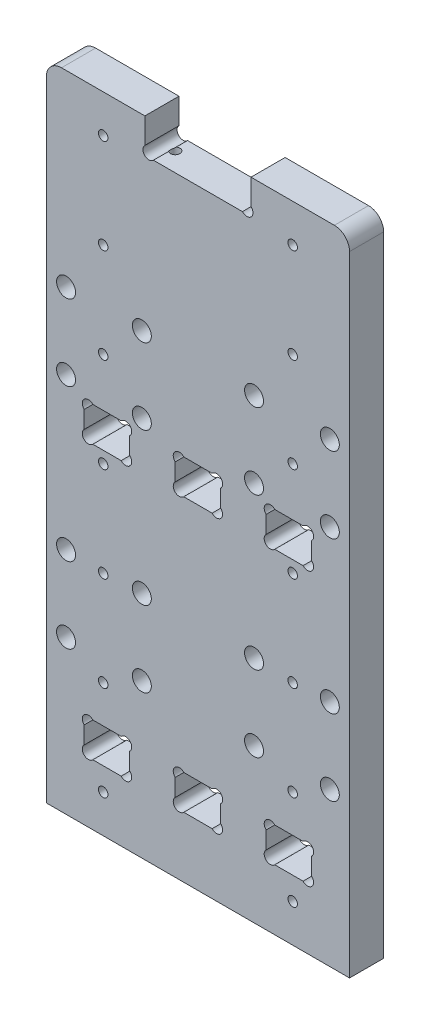
SolidWorks part; units mm, degrees
ref_plane "Front" through (0, 0, 0) normal (0, 0, 1) x (1, 0, 0)
ref_plane "Top" through (0, 0, 0) normal (0, 1, 0) x (1, 0, 0)
ref_plane "Right" through (0, 0, 0) normal (1, 0, 0) x (0, 0, -1)
sketch "Esquisse1" plane through (0, 0, 0) normal (0, 0, 1) x (1, 0, 0)
  line L1 (0, 0) -> (80, 0)
  line L2 (0, 0) -> (0, 170)
  line L3 (0, 170) -> (80, 170)
  line L4 (80, 0) -> (80, 170)
  dimension "D1" = 80
  dimension "D2" = 170
extrude "Boss.-Extru.1" add sketch "Esquisse1" along normal blind 9
sketch "Esquisse2" plane through (0, 0, 9) normal (0, 0, 1) x (1, 0, 0)
  line L0 (40, 0) -> (40, 170) construction
  line L1 (0, 0) -> (80, 0) construction
  line L2 (80, 170) -> (0, 170) construction
  line L3 (15, 10) -> (15, 35) construction
  circle A0 centre (15, 10) radius 1.25
  circle A1 centre (65, 10) radius 1.25
  circle A2 centre (15, 35) radius 1.25
  circle A3 centre (65, 35) radius 1.25
  circle A4 centre (15, 60) radius 1.25
  circle A5 centre (65, 60) radius 1.25
  circle A6 centre (15, 85) radius 1.25
  circle A7 centre (65, 85) radius 1.25
  circle A8 centre (15, 110) radius 1.25
  circle A9 centre (65, 110) radius 1.25
  circle A10 centre (15, 135) radius 1.25
  circle A11 centre (65, 135) radius 1.25
  circle A12 centre (15, 160) radius 1.25
  circle A13 centre (65, 160) radius 1.25
  circle A14 centre (15, 185) radius 1.25
  circle A15 centre (65, 185) radius 1.25
  dimension "D2" = 2.5
  dimension "D1" = 50
  dimension "D3" = 10
  dimension "D5" = 25
  dimension "D4" = 8
extrude "Enlèv. mat.-Extru.1" cut sketch "Esquisse2" against normal through all
sketch "Esquisse4" plane through (0, 0, 9) normal (0, 0, 1) x (1, 0, 0)
  line L0 (40, 170) -> (40, 161) construction
  line L1 (80, 170) -> (0, 170) construction
  line L2 (54, 161) -> (26, 161)
  line L3 (26, 161) -> (26, 170)
  line L4 (26, 170) -> (54, 170)
  line L5 (54, 161) -> (54, 170)
  dimension "D1" = 28
  dimension "D2" = 9
extrude "Enlèv. mat.-Extru.3" cut sketch "Esquisse4" against normal through all
sketch "Esquisse5" plane through (0, 161, 0) normal (0, 1, 0) x (1, 0, 0)
  line L0 (29, 0) -> (29, -4) construction
  line L1 (26, 0) -> (54, 0) construction
  line L2 (40, 0) -> (40, -4.3659) construction
  circle A0 centre (29, -4) radius 1.25
  circle A1 centre (51, -4) radius 1.25
  dimension "D1" = 2.5
  dimension "D2" = 4
  dimension "D3" = 22
extrude "Enlèv. mat.-Extru.4" cut sketch "Esquisse5" against normal blind 10
sketch "Esquisse6" plane through (0, 0, 9) normal (0, 0, 1) x (1, 0, 0)
  line L0 (74.8, 120.5) -> (74.8, 80.5) construction
  line L1 (40, 161) -> (40, 0) construction
  line L2 (26, 161) -> (54, 161) construction
  line L3 (0, 0) -> (80, 0) construction
  line L5 (74.8, 80.5) -> (40, 80.5) construction
  line L6 (5.2, 120.5) -> (5.2, 80.5) construction
  line L7 (74.8, 120.5) -> (64.8, 120.5) construction
  line L8 (64.8, 120.5) -> (64.8, 124.5729) construction
  circle A0 centre (74.8, 120.5) radius 2.5
  circle A1 centre (74.8, 60.5) radius 2.5
  circle A2 centre (74.8, 100.5) radius 2.5
  circle A3 centre (74.8, 40.5) radius 2.5
  circle A4 centre (5.2, 40.5) radius 2.5
  circle A5 centre (5.2, 100.5) radius 2.5
  circle A6 centre (5.2, 60.5) radius 2.5
  circle A7 centre (5.2, 120.5) radius 2.5
  circle A8 centre (54.8, 100.5) radius 2.5
  circle A9 centre (54.8, 120.5) radius 2.5
  circle A10 centre (54.8, 40.5) radius 2.5
  circle A11 centre (54.8, 60.5) radius 2.5
  circle A12 centre (25.2, 60.5) radius 2.5
  circle A13 centre (25.2, 40.5) radius 2.5
  circle A14 centre (25.2, 120.5) radius 2.5
  circle A15 centre (25.2, 100.5) radius 2.5
  dimension "D3" = 5
  dimension "D5" = 20
  dimension "D1" = 34.8
  dimension "D2" = 20
  dimension "D4" = 20
extrude "Enlèv. mat.-Extru.5" cut sketch "Esquisse6" against normal through all
fillet "Congé1" radius 4 2 edges at (80, 170, 4.5) (0, 170, 4.5)
sketch "Esquisse7" plane through (0, 0, 9) normal (0, 0, 1) x (1, 0, 0)
  line L0 (40, 0) -> (40, 161) construction
  line L1 (10, 25.1) -> (22, 25.1)
  line L2 (10, 25.1) -> (10, 16)
  line L3 (10, 16) -> (22, 16)
  line L4 (22, 25.1) -> (22, 16)
  line L5 (0, 0) -> (80, 0) construction
  line L6 (26, 161) -> (54, 161) construction
  line L7 (46, 25.1) -> (34, 25.1)
  line L8 (34, 25.1) -> (34, 16)
  line L9 (34, 16) -> (46, 16)
  line L10 (46, 25.1) -> (46, 16)
  line L11 (58, 25.1) -> (58, 16)
  line L12 (70, 16) -> (58, 16)
  line L13 (70, 25.1) -> (70, 16)
  line L14 (70, 25.1) -> (58, 25.1)
  line L15 (16, 25.1) -> (16, 88.1) construction
  line L16 (16, 56.6) -> (27.6071, 56.6) construction
  line L17 (70, 88.1) -> (58, 88.1)
  line L18 (70, 88.1) -> (70, 97.2)
  line L19 (70, 97.2) -> (58, 97.2)
  line L20 (58, 88.1) -> (58, 97.2)
  line L21 (46, 88.1) -> (46, 97.2)
  line L22 (34, 97.2) -> (46, 97.2)
  line L23 (34, 88.1) -> (34, 97.2)
  line L24 (46, 88.1) -> (34, 88.1)
  line L25 (22, 88.1) -> (22, 97.2)
  line L26 (10, 97.2) -> (22, 97.2)
  line L27 (10, 88.1) -> (10, 97.2)
  line L28 (10, 88.1) -> (22, 88.1)
  point P14 (34, 20.55)
  point P16 (40, 16)
  point P17 (40, 25.1)
  point P37 (40, 88.1)
  point P38 (40, 97.2)
  dimension "D1" = 12
  dimension "D2" = 12
  dimension "D3" = 12
  dimension "D4" = 16
  dimension "D5" = 9.1
  dimension "D6" = 63
extrude "Enlèv. mat.-Extru.6" cut sketch "Esquisse7" against normal through all
sketch "Esquisse8" plane through (0, 0, 9) normal (0, 0, 1) x (1, 0, 0)
  line L0 (10, 16) -> (10, 15.9) construction
  line L1 (10, 16) -> (9.9, 16) construction
  line L2 (10, 16) -> (11.0803, 17.0803) construction
  line L3 (10, 16) -> (22, 16) construction
  line L4 (16, 16) -> (16, 25.1) construction
  line L5 (22, 25.1) -> (10, 25.1) construction
  line L6 (16, 20.55) -> (10, 20.55) construction
  line L7 (10, 25.1) -> (10, 16) construction
  line L8 (10, 25.1) -> (11.0803, 24.0197) construction
  line L9 (10, 25.1) -> (9.9, 25.1) construction
  line L10 (10, 25.1) -> (10, 25.2) construction
  line L11 (22, 25.1) -> (22, 25.2) construction
  line L12 (22, 25.1) -> (22.1, 25.1) construction
  line L13 (22, 25.1) -> (20.9197, 24.0197) construction
  line L14 (22, 16) -> (20.9197, 17.0803) construction
  line L15 (22, 16) -> (22.1, 16) construction
  line L16 (22, 16) -> (22, 15.9) construction
  line L17 (22, 20.55) -> (34, 20.55) construction
  line L18 (22, 16) -> (22, 25.1) construction
  line L19 (34, 25.1) -> (34, 16) construction
  line L20 (40, 16) -> (40, 25.1) construction
  line L21 (34, 16) -> (46, 16) construction
  line L22 (46, 25.1) -> (34, 25.1) construction
  line L23 (28, 20.55) -> (28, 29.7274) construction
  line L24 (34, 16) -> (34, 15.9) construction
  line L25 (34, 16) -> (33.9, 16) construction
  line L26 (34, 16) -> (35.0803, 17.0803) construction
  line L27 (34, 25.1) -> (35.0803, 24.0197) construction
  line L28 (34, 25.1) -> (33.9, 25.1) construction
  line L29 (34, 25.1) -> (34, 25.2) construction
  line L30 (46, 25.1) -> (46, 25.2) construction
  line L31 (46, 25.1) -> (46.1, 25.1) construction
  line L32 (46, 25.1) -> (44.9197, 24.0197) construction
  line L33 (46, 16) -> (44.9197, 17.0803) construction
  line L34 (46, 16) -> (46.1, 16) construction
  line L35 (46, 16) -> (46, 15.9) construction
  line L36 (58, 20.55) -> (46, 20.55) construction
  line L37 (58, 16) -> (58, 15.9) construction
  line L38 (58, 16) -> (57.9, 16) construction
  line L39 (58, 16) -> (59.0803, 17.0803) construction
  line L40 (58, 25.1) -> (59.0803, 24.0197) construction
  line L41 (58, 25.1) -> (57.9, 25.1) construction
  line L42 (58, 25.1) -> (58, 25.2) construction
  line L43 (70, 25.1) -> (70, 25.2) construction
  line L44 (70, 25.1) -> (70.1, 25.1) construction
  line L45 (70, 25.1) -> (68.9197, 24.0197) construction
  line L46 (64, 20.55) -> (70, 20.55) construction
  line L47 (64, 16) -> (64, 25.1) construction
  line L48 (70, 16) -> (68.9197, 17.0803) construction
  line L49 (70, 16) -> (70.1, 16) construction
  line L50 (70, 16) -> (70, 15.9) construction
  line L51 (16, 25.1) -> (16, 88.1) construction
  line L52 (10, 88.1) -> (22, 88.1) construction
  line L53 (16, 56.6) -> (40, 56.6) construction
  line L54 (70, 97.2) -> (70, 97.3) construction
  line L55 (70, 97.2) -> (70.1, 97.2) construction
  line L56 (70, 97.2) -> (68.9197, 96.1197) construction
  line L57 (64, 97.2) -> (64, 88.1) construction
  line L58 (64, 92.65) -> (70, 92.65) construction
  line L59 (70, 88.1) -> (68.9197, 89.1803) construction
  line L60 (70, 88.1) -> (70.1, 88.1) construction
  line L61 (70, 88.1) -> (70, 88) construction
  line L62 (58, 88.1) -> (58, 88) construction
  line L63 (58, 88.1) -> (57.9, 88.1) construction
  line L64 (58, 88.1) -> (59.0803, 89.1803) construction
  line L65 (58, 97.2) -> (59.0803, 96.1197) construction
  line L66 (58, 97.2) -> (57.9, 97.2) construction
  line L67 (58, 97.2) -> (58, 97.3) construction
  line L68 (58, 92.65) -> (46, 92.65) construction
  line L69 (46, 97.2) -> (46, 97.3) construction
  line L70 (46, 97.2) -> (46.1, 97.2) construction
  line L71 (46, 97.2) -> (44.9197, 96.1197) construction
  line L72 (46, 88.1) -> (44.9197, 89.1803) construction
  line L73 (46, 88.1) -> (46.1, 88.1) construction
  line L74 (46, 88.1) -> (46, 88) construction
  line L75 (34, 88.1) -> (34, 88) construction
  line L76 (34, 88.1) -> (33.9, 88.1) construction
  line L77 (34, 88.1) -> (35.0803, 89.1803) construction
  line L78 (34, 97.2) -> (35.0803, 96.1197) construction
  line L79 (34, 97.2) -> (33.9, 97.2) construction
  line L80 (34, 97.2) -> (34, 97.3) construction
  line L81 (40, 97.2) -> (40, 88.1) construction
  line L82 (22, 92.65) -> (34, 92.65) construction
  line L83 (22, 97.2) -> (22, 97.3) construction
  line L84 (22, 97.2) -> (22.1, 97.2) construction
  line L86 (22, 88.1) -> (20.9197, 89.1803) construction
  line L87 (22, 88.1) -> (22.1, 88.1) construction
  line L88 (22, 88.1) -> (22, 88) construction
  line L89 (10, 88.1) -> (10, 88) construction
  line L90 (10, 88.1) -> (9.9, 88.1) construction
  line L91 (10, 88.1) -> (11.0803, 89.1803) construction
  line L92 (16, 92.65) -> (10, 92.65) construction
  line L93 (16, 97.2) -> (16, 88.1) construction
  line L94 (10, 97.2) -> (11.0803, 96.1197) construction
  line L95 (10, 97.2) -> (9.9, 97.2) construction
  line L96 (10, 97.2) -> (10, 97.3) construction
  line L97 (26, 161) -> (26, 160.9) construction
  line L98 (26, 161) -> (25.9, 161) construction
  line L99 (40, 161) -> (40, 171.5112) construction
  line L100 (26, 161) -> (54, 161) construction
  line L101 (54, 161) -> (54.1, 161) construction
  line L102 (54, 161) -> (54, 160.9) construction
  circle A0 centre (11.0803, 17.0803) radius 1.6
  circle A1 centre (11.0803, 24.0197) radius 1.6
  circle A2 centre (20.9197, 24.0197) radius 1.6
  circle A3 centre (20.9197, 17.0803) radius 1.6
  circle A4 centre (35.0803, 17.0803) radius 1.6
  circle A5 centre (35.0803, 24.0197) radius 1.6
  circle A6 centre (44.9197, 24.0197) radius 1.6
  circle A7 centre (44.9197, 17.0803) radius 1.6
  circle A8 centre (59.0803, 17.0803) radius 1.6
  circle A9 centre (59.0803, 24.0197) radius 1.6
  circle A10 centre (68.9197, 24.0197) radius 1.6
  circle A11 centre (68.9197, 17.0803) radius 1.6
  circle A12 centre (68.9197, 96.1197) radius 1.6
  circle A13 centre (68.9197, 89.1803) radius 1.6
  circle A14 centre (59.0803, 89.1803) radius 1.6
  circle A15 centre (59.0803, 96.1197) radius 1.6
  circle A16 centre (44.9197, 96.1197) radius 1.6
  circle A17 centre (44.9197, 89.1803) radius 1.6
  circle A18 centre (35.0803, 89.1803) radius 1.6
  circle A19 centre (35.0803, 96.1197) radius 1.6
  circle A20 centre (20.9197, 96.1197) radius 1.6
  circle A21 centre (20.9197, 89.1803) radius 1.6
  circle A22 centre (11.0803, 89.1803) radius 1.6
  circle A23 centre (11.0803, 96.1197) radius 1.6
  circle A24 centre (27.0803, 162.0803) radius 1.6
  circle A25 centre (52.9197, 162.0803) radius 1.6
  point P184 (22, 97.2)
  point P186 (10, 97.2)
  point P188 (10, 88.1)
  point P190 (34, 97.2)
  point P192 (58, 97.2)
  point P194 (70, 97.2)
  dimension "D1" = 3.2
  dimension "D2" = 45
  dimension "D3" = 0.1
  dimension "D5" = 0.1
extrude "Enlèv. mat.-Extru.7" cut sketch "Esquisse8" against normal through all
